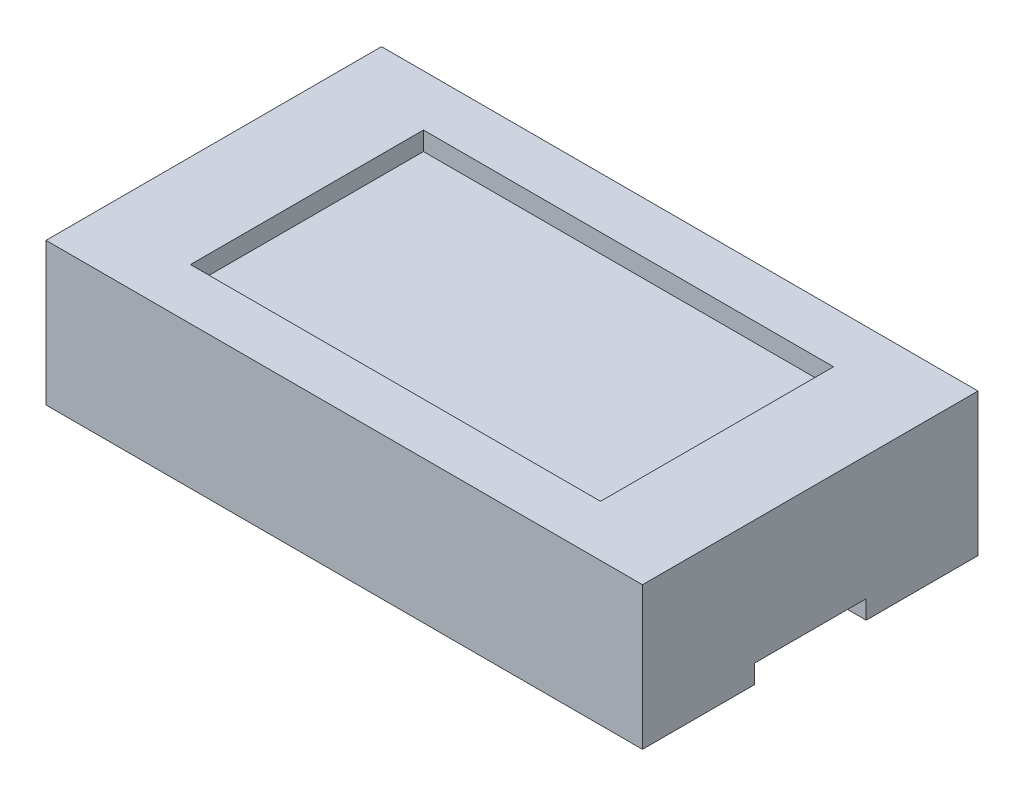
SolidWorks part; units mm, degrees
ref_plane "前视基准面" through (0, 0, 0) normal (0, 0, 1) x (1, 0, 0)
ref_plane "上视基准面" through (0, 0, 0) normal (0, 1, 0) x (1, 0, 0)
ref_plane "右视基准面" through (0, 0, 0) normal (1, 0, 0) x (0, 0, -1)
other "Configuration Table"
sketch "草图1" plane through (0, 0, 0) normal (0, 1, 0) x (1, 0, 0)
  line L1 (-32, -18) -> (32, -18)
  line L2 (-32, -18) -> (-32, 18)
  line L3 (-32, 18) -> (32, 18)
  line L4 (32, -18) -> (32, 18)
  line L5 (-32, -18) -> (32, 18) construction
  line L6 (-32, 18) -> (32, -18) construction
  point P0 (0, 0)
  dimension "D1" = 64
  dimension "D2" = 36
extrude "凸台-拉伸1" add sketch "草图1" along normal blind 15.3
sketch "草图2" plane through (0, 15.3, 0) normal (0, 1, 0) x (1, 0, 0)
  line L1 (-22, -12.5) -> (22, -12.5)
  line L2 (-22, -12.5) -> (-22, 12.5)
  line L3 (-22, 12.5) -> (22, 12.5)
  line L4 (22, -12.5) -> (22, 12.5)
  line L5 (-22, -12.5) -> (22, 12.5) construction
  line L6 (-22, 12.5) -> (22, -12.5) construction
  point P0 (0, 0)
  dimension "D1" = 44
  dimension "D2" = 25
extrude "切除-拉伸1" cut sketch "草图2" against normal blind 2
sketch "草图3" plane through (0, 0, 0) normal (0, -1, 0) x (1, 0, 0)
  line L0 (32, 6) -> (16, 6)
  line L1 (32, 18) -> (32, -18) construction
  line L2 (16, 6) -> (16, -6)
  line L3 (16, 0) -> (32, 0)
  line L4 (32, -6) -> (32, 6)
  line L5 (0, 0) -> (41.0632, 0) construction
  line L6 (32, -6) -> (16, -6)
  line M6 (32, -18) -> (32, 18)
  dimension "D1" = 6
  dimension "D2" = 16
extrude "切除-拉伸2" cut sketch "草图3" against normal blind 2 contours L6 L3 L2 M6 | L2 L3 L0 M6
